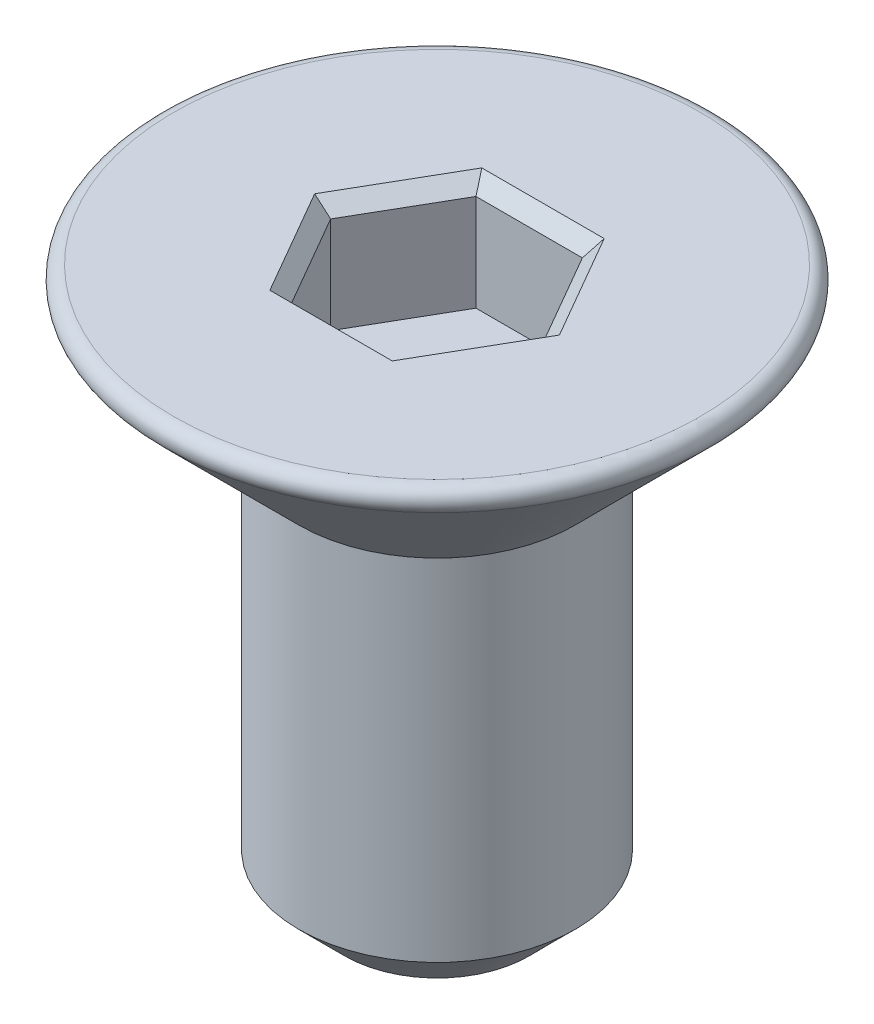
SolidWorks part; units mm, degrees
material "AISI Acier inoxydable type 316L"
ref_plane "Plan de face" through (0, 0, 0) normal (0, 0, 1) x (1, 0, 0)
ref_plane "Plan de dessus" through (0, 0, 0) normal (0, 1, 0) x (1, 0, 0)
ref_plane "Plan de droite" through (0, 0, 0) normal (1, 0, 0) x (0, 0, -1)
sketch "Esquisse1" plane through (0, 0, 0) normal (0, 0, 1) x (1, 0, 0)
  line L0 (0, 6.973) -> (0, -16.342) construction
  line L1 (1.5, -5.5) -> (1, -6)
  line L2 (0, 0) -> (2.8586, 0)
  line L4 (2.9586, -0.2414) -> (1.5, -1.7)
  line L5 (1.5, -1.7) -> (1.5, -5.5)
  line L7 (1, -6) -> (0, -6)
  line L8 (0, -6) -> (0, 0)
  arc A0 (2.8586, 0) -> (2.9586, -0.2414) centre (2.8586, -0.1414) cw
  point P7 (0, 0)
  point P9 (1.5, -6)
  dimension "D5" = 45
  dimension "D1" = 1.7
  dimension "D2" = 6
  dimension "D3" = 3
  dimension "D4" = 6
revolve "Révolution1" add sketch "Esquisse1" angle 360 about L0
cosmetic thread "Représentation de filetage1" parameters "D2"=2.439
sketch "Esquisse2" plane through (0, 0, 0) normal (0, 1, 0) x (1, 0, 0)
  line L0 (-1.1547, 0) -> (-0.5774, -1)
  line L1 (1.1547, 0) -> (0.5774, 1)
  line L2 (0.5774, 1) -> (-0.5774, 1)
  line L3 (-0.5774, 1) -> (-1.1547, 0)
  line L4 (-0.5774, -1) -> (0.5774, -1)
  line L5 (0.5774, -1) -> (1.1547, 0)
  circle A0 centre (0, 0) radius 1 construction
  dimension "D1" = 2
extrude "Enlèv. mat.-Extru.1" cut sketch "Esquisse2" against normal blind 1.2
chamfer "Chanfrein1" distance 0.15 angle 45 6 edges at (-0.866, 0, -0.5) (-0.866, 0, 0.5) (0, 0, 1) (0.866, 0, 0.5) (0.866, 0, -0.5) (0, 0, -1)
